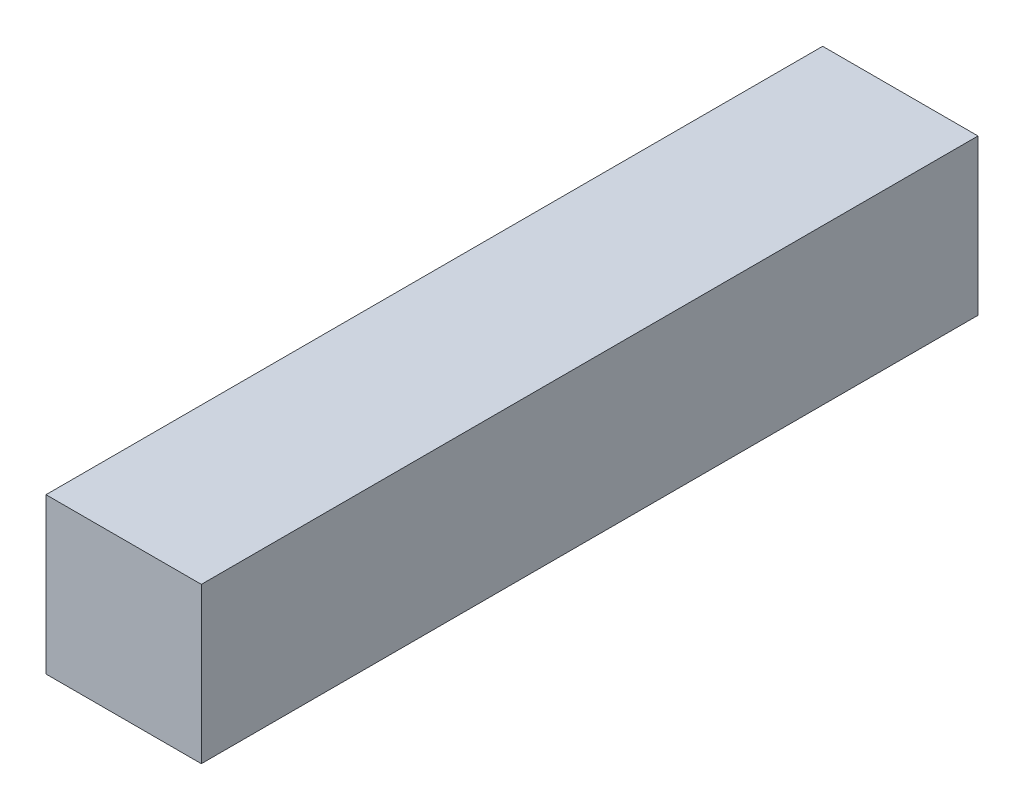
SolidWorks part; units mm, degrees
ref_plane "Front Plane" through (0, 0, 0) normal (0, 0, 1) x (1, 0, 0)
ref_plane "Top Plane" through (0, 0, 0) normal (0, 1, 0) x (1, 0, 0)
ref_plane "Right Plane" through (0, 0, 0) normal (1, 0, 0) x (0, 0, -1)
other "Configuration Table"
sketch "Sketch1" plane through (0, 0, 0) normal (0, 0, 1) x (1, 0, 0)
  line L1 (0, 0) -> (25.4, 0)
  line L2 (0, 0) -> (0, 25.4)
  line L3 (0, 25.4) -> (25.4, 25.4)
  line L4 (25.4, 0) -> (25.4, 25.4)
  dimension "D1" = 25.4
  dimension "D2" = 25.4
extrude "Extrude1" add sketch "Sketch1" along normal blind 127
